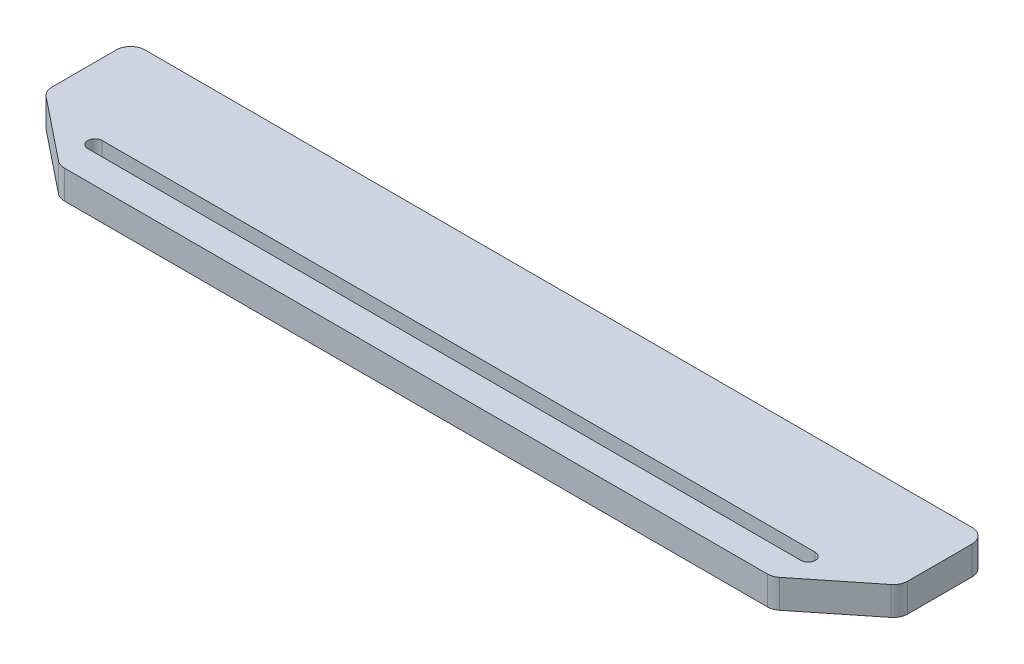
SolidWorks part; units mm, degrees
material "6061 Alloy"
ref_plane "Front Plane" through (0, 0, 0) normal (0, 0, 1) x (1, 0, 0)
ref_plane "Top Plane" through (0, 0, 0) normal (0, 1, 0) x (1, 0, 0)
ref_plane "Right Plane" through (0, 0, 0) normal (1, 0, 0) x (0, 0, -1)
sketch "Sketch1" plane through (0, 0, 0) normal (0, 1, 0) x (1, 0, 0)
  line L0 (0, -5) -> (0, -27.5969)
  line L3 (5, 0) -> (295, 0)
  line L5 (300, -5) -> (300, -27.5969)
  line L6 (1.8765, -31.5012) -> (23.6304, -48.9043)
  line L7 (26.7539, -50) -> (273.2461, -50)
  line L8 (276.3696, -48.9043) -> (298.1235, -31.5012)
  arc A0 (300, -5) -> (295, 0) centre (295, -5) ccw
  arc A1 (0, -5) -> (5, 0) centre (5, -5) cw
  arc A2 (23.6304, -48.9043) -> (26.7539, -50) centre (26.7539, -45) ccw
  arc A3 (276.3696, -48.9043) -> (273.2461, -50) centre (273.2461, -45) cw
  arc A4 (300, -27.5969) -> (298.1235, -31.5012) centre (295, -27.5969) cw
  arc A5 (1.8765, -31.5012) -> (0, -27.5969) centre (5, -27.5969) cw
  point P0 (0, 0)
  point P2 (150, 0)
  point P6 (150, -50)
  point P12 (300, 0)
  point P15 (0, 0)
  point P18 (25, -50)
  point P21 (275, -50)
  point P24 (300, -30)
  point P28 (0, -30)
  dimension "D5" = 5
  dimension "D6" = 5
  dimension "D1" = 300
  dimension "D2" = 250
  dimension "D3" = 30
  dimension "D4" = 20
extrude "Boss-Extrude1" add sketch "Sketch1" along normal blind 10
sketch "Sketch2" plane through (0, 0, 0) normal (0, 1, 0) x (1, 0, 0)
  line L0 (26.7539, -50) -> (273.2461, -50) construction
  line L1 (25, -37.5) -> (275, -37.5) construction
  line L2 (25, -35) -> (275, -35)
  line L3 (25, -40) -> (275, -40)
  line L6 (5, 0) -> (295, 0) construction
  line L7 (150, 0) -> (150, -60.0142) construction
  arc A0 (25, -35) -> (25, -40) centre (25, -37.5) ccw
  arc A1 (275, -40) -> (275, -35) centre (275, -37.5) ccw
  point P6 (150, -37.5)
  dimension "D1" = 5
  dimension "D2" = 250
  dimension "D3" = 10
extrude "Cut-Extrude4" cut sketch "Sketch2" against normal through all and the other way through all
